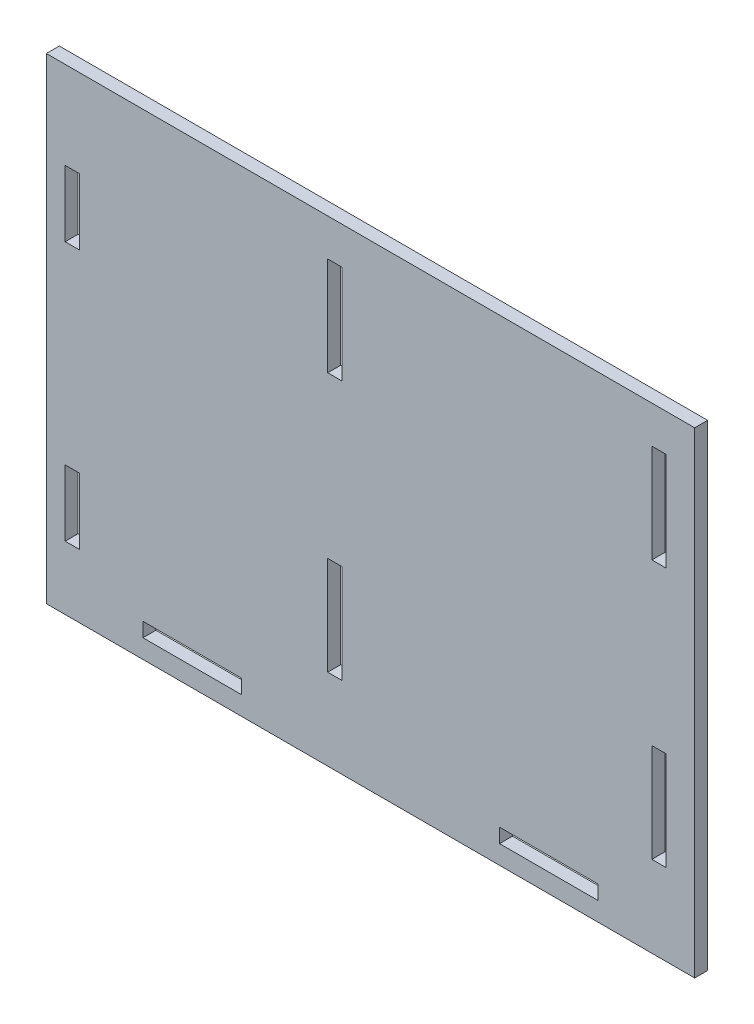
SolidWorks part; units mm, degrees
ref_plane "Спереди" through (0, 0, 0) normal (0, 0, 1) x (1, 0, 0)
ref_plane "Сверху" through (0, 0, 0) normal (0, 1, 0) x (1, 0, 0)
ref_plane "Справа" through (0, 0, 0) normal (1, 0, 0) x (0, 0, -1)
sketch "Эскиз1" plane through (0, 0, 0) normal (0, 0, 1) x (1, 0, 0)
  line L0 (0, 0) -> (0, 147)
  line L1 (0, 0) -> (200, 0)
  line L2 (200, 0) -> (200, 147)
  line L3 (200, 147) -> (0, 147)
  line L4 (100, 0) -> (100, 42.511) construction
  line L13 (200, 73.5) -> (159.4478, 73.5) construction
  line L14 (0, 73.5) -> (18.3539, 73.5) construction
  line L15 (10.2, 19.6) -> (5.8, 19.6)
  line L16 (139.8, 10.2) -> (170.2, 10.2)
  line L17 (139.8, 10.2) -> (139.8, 5.8)
  line L18 (139.8, 5.8) -> (170.2, 5.8)
  line L19 (170.2, 10.2) -> (170.2, 5.8)
  line L20 (5.8, 40) -> (5.8, 19.6)
  line L21 (10.2, 40) -> (5.8, 40)
  line L22 (10.2, 40) -> (10.2, 19.6)
  line L23 (60.2, 5.8) -> (29.8, 5.8)
  line L24 (29.8, 10.2) -> (29.8, 5.8)
  line L25 (60.2, 10.2) -> (29.8, 10.2)
  line L26 (60.2, 10.2) -> (60.2, 5.8)
  line L31 (5.8, 99.6) -> (5.8, 40) construction
  line L32 (5.8, 99.6) -> (10.2, 99.6)
  line L33 (5.8, 99.6) -> (5.8, 120)
  line L34 (5.8, 120) -> (10.2, 120)
  line L35 (10.2, 99.6) -> (10.2, 120)
  line L36 (45, 10.2) -> (45, 5.8) construction
  line L37 (155, 10.2) -> (155, 5.8) construction
  line L38 (5.8, 29.8) -> (10.2, 29.8) construction
  line L39 (5.8, 109.8) -> (10.2, 109.8) construction
  line L40 (186.8, 120.3) -> (191.2, 120.3) construction
  line L41 (186.8, 25.1) -> (191.2, 25.1)
  line L42 (186.8, 25.1) -> (186.8, 55.5)
  line L43 (186.8, 55.5) -> (191.2, 55.5)
  line L44 (191.2, 25.1) -> (191.2, 55.5)
  line L45 (186.8, 135.5) -> (191.2, 135.5)
  line L46 (186.8, 135.5) -> (186.8, 105.1)
  line L47 (186.8, 105.1) -> (191.2, 105.1)
  line L48 (191.2, 135.5) -> (191.2, 105.1)
  line L49 (186.8, 40.3) -> (191.2, 40.3) construction
  line L50 (189, 25.1) -> (189, 40.3) construction
  line L51 (189, 105.1) -> (189, 117.8713) construction
  line L52 (8, 19.6) -> (8, 40) construction
  line L53 (8, 99.6) -> (8, 120) construction
  line L54 (170.2, 8) -> (179.1102, 8) construction
  line L55 (86.8, 135.5) -> (86.8, 105.1)
  line L56 (86.8, 135.5) -> (91.2, 135.5)
  line L57 (91.2, 135.5) -> (91.2, 105.1)
  line L58 (86.8, 105.1) -> (91.2, 105.1)
  line L59 (86.8, 25.1) -> (86.8, 55.5)
  line L60 (86.8, 25.1) -> (91.2, 25.1)
  line L61 (91.2, 25.1) -> (91.2, 55.5)
  line L62 (86.8, 55.5) -> (91.2, 55.5)
  line L63 (89, 135.5) -> (89, 105.1) construction
  point P51 (189, 111.4857)
  dimension "D1" = 147
  dimension "D2" = 147
  dimension "D3" = 200
  dimension "D4" = 30.4
  dimension "D5" = 30.4
  dimension "D6" = 29.8
  dimension "D7" = 4.4
  dimension "D8" = 8
  dimension "D9" = 30.4
  dimension "D10" = 110
  dimension "D11" = 4.4
  dimension "D12" = 4.4
  dimension "D13" = 20.4
  dimension "D14" = 80
  dimension "D15" = 4.4
  dimension "D16" = 40.3
  dimension "D17" = 80
  dimension "D18" = 11
  dimension "D19" = 11
  dimension "D20" = 20.4
  dimension "D21" = 8
  dimension "D22" = 4.4
  dimension "D24" = 100
  dimension "D23" = 2
extrude "Бобышка-Вытянуть1" add sketch "Эскиз1" along normal blind 4
